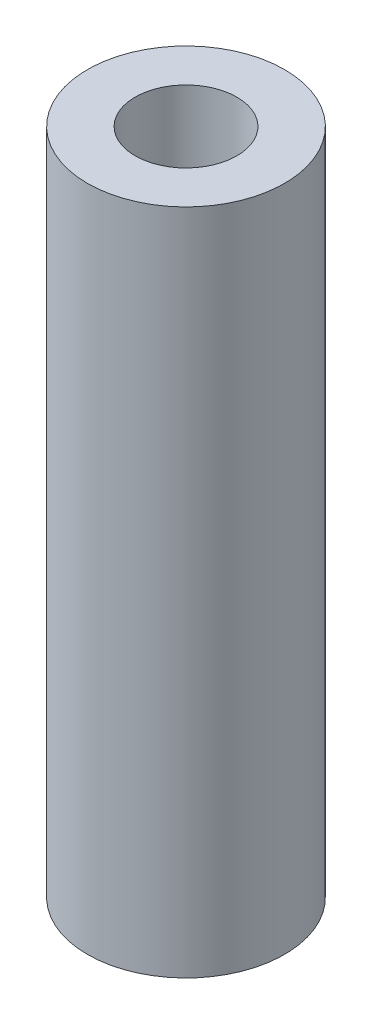
SolidWorks part; units mm, degrees
ref_plane "Front Plane" through (0, 0, 0) normal (0, 0, 1) x (1, 0, 0)
ref_plane "Top Plane" through (0, 0, 0) normal (0, 1, 0) x (1, 0, 0)
ref_plane "Right Plane" through (0, 0, 0) normal (1, 0, 0) x (0, 0, -1)
sketch "Sketch1" plane through (0, 0, 0) normal (0, 1, 0) x (1, 0, 0)
  circle A0 centre (0, 0) radius 1.6
  circle A1 centre (0, 0) radius 3.1
  dimension "D1" = 3.2
  dimension "D2" = 1.5
extrude "Boss-Extrude1" add sketch "Sketch1" along normal blind 21
